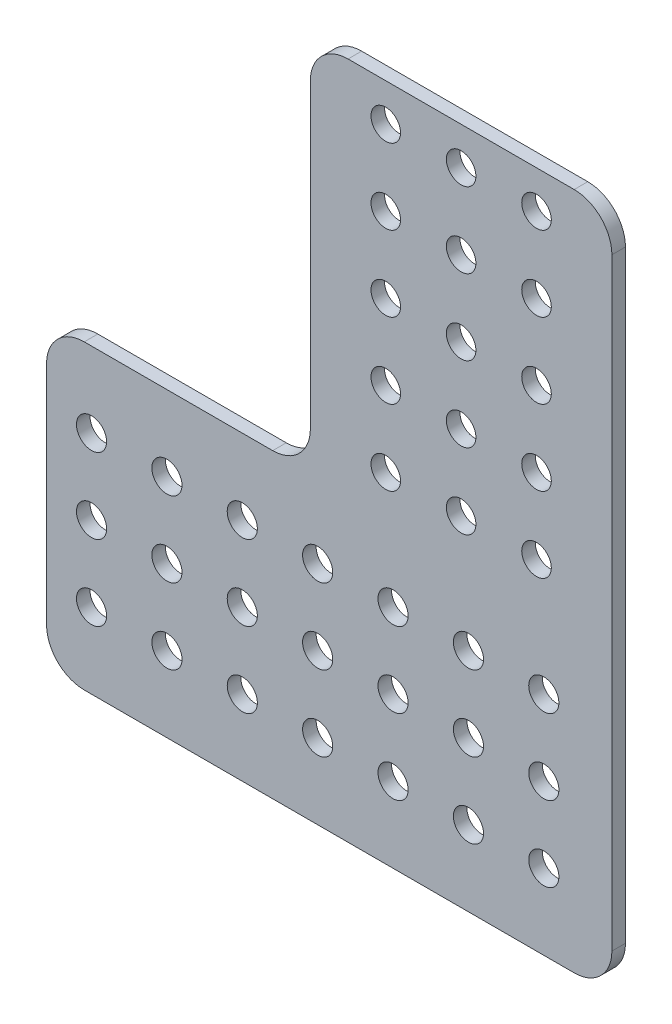
SolidWorks part; units mm, degrees
ref_plane "Front Plane" through (0, 0, 0) normal (0, 0, 1) x (1, 0, 0)
ref_plane "Top Plane" through (0, 0, 0) normal (0, 1, 0) x (1, 0, 0)
ref_plane "Right Plane" through (0, 0, 0) normal (1, 0, 0) x (0, 0, -1)
sketch "Sketch1" plane through (0, 0, -219.6085) normal (0, 0, -1) x (-1, 0, 0)
  line L0 (77.5366, 159.0008) -> (77.5366, 108.2008)
  line L1 (83.8866, 159.0008) -> (83.8866, 108.2008) construction
  line L6 (-17.7134, 222.5008) -> (-17.7134, 108.2008)
  line L7 (33.0866, 222.5008) -> (-17.7134, 222.5008)
  line L8 (33.0866, 159.0008) -> (33.0866, 222.5008)
  line L9 (83.8866, 159.0008) -> (33.0866, 159.0008)
  line L10 (83.8866, 108.2008) -> (83.8866, 159.0008)
  line L11 (-17.7134, 108.2008) -> (83.8866, 108.2008)
  line L12 (-17.7134, 222.5008) -> (-17.7134, 108.2008)
  line L13 (33.0866, 222.5008) -> (-17.7134, 222.5008)
  line L14 (33.0866, 159.0008) -> (33.0866, 222.5008)
  line L15 (77.5366, 159.0008) -> (33.0866, 159.0008)
  line L17 (-17.7134, 108.2008) -> (77.5366, 108.2008)
  circle A1 centre (44.5534, 120.9008) radius 2.54
  circle A2 centre (44.5534, 120.9008) radius 2.54
  circle A3 centre (57.2578, 133.6008) radius 2.54
  circle A4 centre (57.2578, 133.6008) radius 2.54
  circle A5 centre (69.9578, 146.3008) radius 2.54
  circle A6 centre (69.9578, 146.3008) radius 2.54
  circle A7 centre (69.9578, 133.6008) radius 2.54
  circle A8 centre (69.9578, 133.6008) radius 2.54
  circle A9 centre (69.9578, 120.9008) radius 2.54
  circle A10 centre (69.9578, 120.9008) radius 2.54
  circle A11 centre (57.2534, 120.9008) radius 2.54
  circle A12 centre (57.2534, 120.9008) radius 2.54
  circle A13 centre (20.3866, 165.3508) radius 2.4892
  circle A14 centre (20.3866, 165.3508) radius 2.4892
  circle A15 centre (-6.2422, 146.3008) radius 2.54
  circle A16 centre (-6.2422, 146.3008) radius 2.54
  circle A17 centre (-6.2466, 133.6008) radius 2.54
  circle A18 centre (-6.2466, 133.6008) radius 2.54
  circle A19 centre (6.4578, 146.3008) radius 2.54
  circle A20 centre (6.4578, 146.3008) radius 2.54
  circle A21 centre (6.4534, 133.6008) radius 2.54
  circle A22 centre (6.4534, 133.6008) radius 2.54
  circle A23 centre (19.1578, 146.3008) radius 2.54
  circle A24 centre (19.1578, 146.3008) radius 2.54
  circle A25 centre (-6.2466, 120.9008) radius 2.54
  circle A26 centre (-6.2466, 120.9008) radius 2.54
  circle A27 centre (6.4534, 120.9008) radius 2.54
  circle A28 centre (6.4534, 120.9008) radius 2.54
  circle A29 centre (19.1534, 120.9008) radius 2.54
  circle A30 centre (19.1534, 120.9008) radius 2.54
  circle A31 centre (19.1578, 133.6008) radius 2.54
  circle A32 centre (19.1578, 133.6008) radius 2.54
  circle A33 centre (31.8578, 133.6008) radius 2.54
  circle A34 centre (31.8578, 133.6008) radius 2.54
  circle A35 centre (44.5578, 133.6008) radius 2.54
  circle A36 centre (44.5578, 133.6008) radius 2.54
  circle A37 centre (31.8578, 146.3008) radius 2.54
  circle A38 centre (31.8578, 146.3008) radius 2.54
  circle A39 centre (44.5578, 146.3008) radius 2.54
  circle A40 centre (44.5578, 146.3008) radius 2.54
  circle A41 centre (57.2578, 146.3008) radius 2.54
  circle A42 centre (57.2578, 146.3008) radius 2.54
  circle A43 centre (31.8534, 120.9008) radius 2.54
  circle A44 centre (31.8534, 120.9008) radius 2.54
  circle A45 centre (-5.0134, 216.1508) radius 2.4892
  circle A46 centre (-5.0134, 216.1508) radius 2.4892
  circle A47 centre (7.6866, 216.1508) radius 2.4892
  circle A48 centre (7.6866, 216.1508) radius 2.4892
  circle A49 centre (20.3866, 216.1508) radius 2.4892
  circle A50 centre (20.3866, 216.1508) radius 2.4892
  circle A51 centre (-5.0134, 203.4508) radius 2.4892
  circle A52 centre (-5.0134, 203.4508) radius 2.4892
  circle A53 centre (7.6866, 203.4508) radius 2.4892
  circle A54 centre (7.6866, 203.4508) radius 2.4892
  circle A55 centre (20.3866, 203.4508) radius 2.4892
  circle A56 centre (20.3866, 203.4508) radius 2.4892
  circle A57 centre (-5.0134, 190.7508) radius 2.4892
  circle A58 centre (-5.0134, 190.7508) radius 2.4892
  circle A59 centre (7.6866, 190.7508) radius 2.4892
  circle A60 centre (7.6866, 190.7508) radius 2.4892
  circle A61 centre (20.3866, 190.7508) radius 2.4892
  circle A62 centre (20.3866, 190.7508) radius 2.4892
  circle A63 centre (-5.0134, 178.0508) radius 2.4892
  circle A64 centre (-5.0134, 178.0508) radius 2.4892
  circle A65 centre (7.6866, 178.0508) radius 2.4892
  circle A66 centre (7.6866, 178.0508) radius 2.4892
  circle A67 centre (20.3866, 178.0508) radius 2.4892
  circle A68 centre (20.3866, 178.0508) radius 2.4892
  circle A69 centre (-5.0134, 165.3508) radius 2.4892
  circle A70 centre (-5.0134, 165.3508) radius 2.4892
  circle A71 centre (7.6866, 165.3508) radius 2.4892
  circle A72 centre (7.6866, 165.3508) radius 2.4892
  dimension "D38" = 6.35
  dimension "D1" = 0
  dimension "D2" = 0
  dimension "D3" = 0
  dimension "D4" = 0
  dimension "D5" = 0
  dimension "D6" = 0
  dimension "D7" = 0
  dimension "D8" = 0
  dimension "D9" = 0
  dimension "D10" = 0
  dimension "D11" = 0
  dimension "D12" = 0
  dimension "D13" = 0
  dimension "D14" = 0
  dimension "D15" = 0
  dimension "D16" = 0
  dimension "D17" = 0
  dimension "D18" = 0
  dimension "D19" = 0
  dimension "D20" = 0
  dimension "D21" = 0
  dimension "D22" = 0
  dimension "D23" = 0
  dimension "D24" = 0
  dimension "D25" = 0
  dimension "D26" = 0
  dimension "D27" = 0
  dimension "D28" = 0
  dimension "D29" = 0
  dimension "D30" = 0
  dimension "D31" = 0
  dimension "D32" = 0
  dimension "D33" = 0
  dimension "D34" = 0
  dimension "D35" = 0
  dimension "D36" = 0
  dimension "D37" = 0
extrude "Boss-Extrude1" add sketch "Sketch1" along normal blind 2.286
fillet "Fillet1" radius 6.35 6 edges at (17.7134, 108.2008, -220.7515) (17.7134, 222.5008, -220.7515) (-33.0866, 159.0008, -220.7515) (-33.0866, 222.5008, -220.7515) (-77.5366, 108.2008, -220.7515) (-77.5366, 159.0008, -220.7515)
